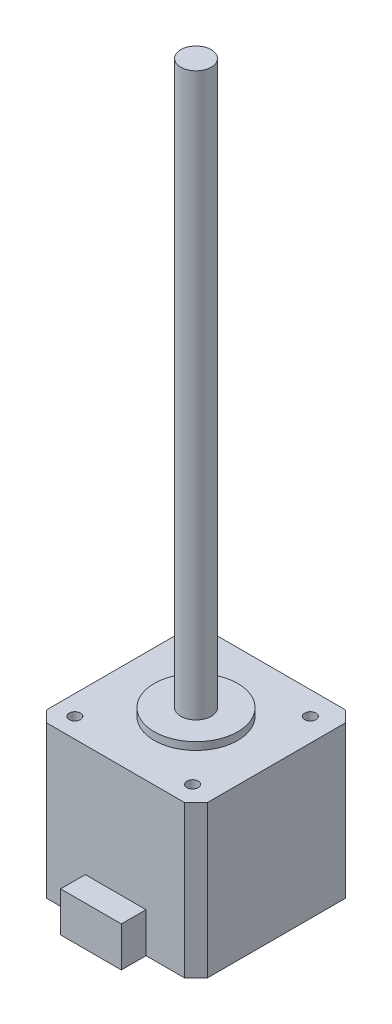
SolidWorks part; units mm, degrees
ref_plane "Alzado" through (0, 0, 0) normal (0, 0, 1) x (1, 0, 0)
ref_plane "Planta" through (0, 0, 0) normal (0, 1, 0) x (1, 0, 0)
ref_plane "Vista lateral" through (0, 0, 0) normal (1, 0, 0) x (0, 0, -1)
sketch "Croquis1" plane through (0, 0, 0) normal (0, 1, 0) x (1, 0, 0)
  line L0 (0, 0) -> (0, 50000) construction
  line L1 (-18.15, -21.15) -> (18.15, -21.15)
  line L2 (-21.15, -18.15) -> (-21.15, 18.15)
  line L3 (-18.15, 21.15) -> (18.15, 21.15)
  line L4 (21.15, -18.15) -> (21.15, 18.15)
  line L5 (-21.15, -21.15) -> (21.15, 21.15) construction
  line L6 (-21.15, 21.15) -> (21.15, -21.15) construction
  line L7 (0, 0) -> (50000, 0) construction
  line L8 (-21.15, 18.15) -> (-18.15, 21.15)
  line L9 (-21.15, -18.15) -> (-18.15, -21.15)
  line L10 (18.15, -21.15) -> (21.15, -18.15)
  line L11 (18.15, 21.15) -> (21.15, 18.15)
  point P0 (0, 0)
extrude "Saliente-Extruir1" add sketch "Croquis1" along normal blind 40
sketch "Croquis2" plane through (0, 40, 0) normal (0, 1, 0) x (1, 0, 0)
  line L0 (0, 0) -> (0, 50000) construction
  line L1 (0, 0) -> (50000, 0) construction
  circle A2 centre (15.05, 15.05) radius 1.5
  circle A3 centre (-15.95, 15.05) radius 1.5
  circle A4 centre (-15.95, -15.95) radius 1.5
  circle A5 centre (15.05, -15.95) radius 1.5
  dimension "D1" = 2
  dimension "D2" = 2
extrude "Cortar-Extruir2" cut sketch "Croquis2" against normal blind 4.5
sketch "Croquis3" plane through (0, 40, 0) normal (0, 1, 0) x (1, 0, 0)
  circle A0 centre (0, 0) radius 11
  circle A1 centre (0, 0) radius 4
extrude "Saliente-Extruir3" add sketch "Croquis3" along normal blind 2
sketch "Croquis8" plane through (0, 40, 0) normal (0, 1, 0) x (1, 0, 0)
  circle A0 centre (0, 0) radius 4
extrude "Saliente-Extruir4" add sketch "Croquis8" along normal blind 150
chamfer "Chaflán1" [suppressed] distance 1 angle 45
sketch "Croquis9" plane through (0, 0, 21.15) normal (0, 0, 1) x (1, 0, 0)
  line L0 (0, 0) -> (0, 50000) construction
  line L1 (-18.15, 0) -> (18.15, 0) construction
  line L2 (0, 0) -> (50000, 0) construction
  line L4 (-8, 0) -> (8, 0)
  line L5 (-8, 0) -> (-8, 10.5)
  line L6 (-8, 10.5) -> (8, 10.5)
  line L7 (8, 0) -> (8, 10.5)
  point P4 (0, 0)
  point P7 (0, 0)
  dimension "D1" = 10.5
  dimension "D2" = 16
extrude "Saliente-Extruir6" add sketch "Croquis9" along normal blind 6.5
sketch "Croquis11" plane through (0, 190, 0) normal (0, 1, 0) x (1, 0, 0)
  circle A1 centre (0, 0) radius 4
  circle A2 centre (0, 0) radius 4
  dimension "D1" = 0
sketch "Croquis12" plane through (0, 190, 0) normal (0, 1, 0) x (1, 0, 0)
  circle A1 centre (0, 0) radius 4
  circle A2 centre (0, 0) radius 4
  dimension "D1" = 0
